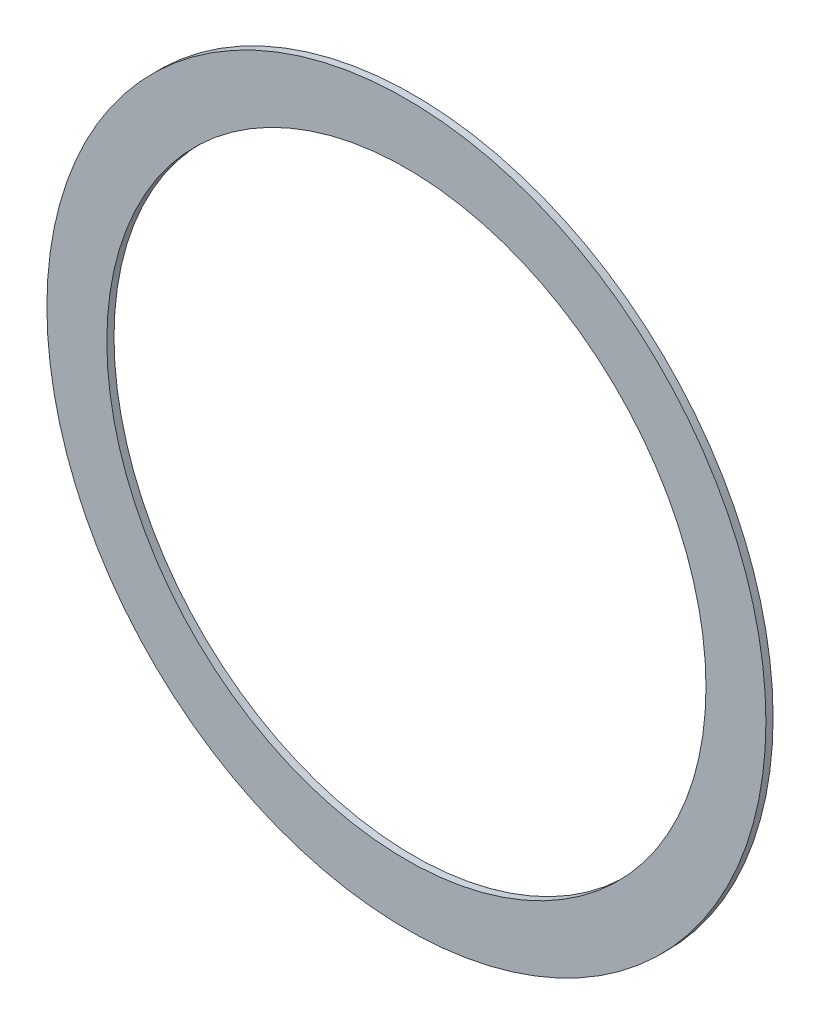
SolidWorks part; units mm, degrees
material "VITON"
ref_plane "Front" through (0, 0, 0) normal (0, 0, 1) x (1, 0, 0)
ref_plane "Top" through (0, 0, 0) normal (0, 1, 0) x (1, 0, 0)
ref_plane "Right" through (0, 0, 0) normal (1, 0, 0) x (0, 0, -1)
sketch "Sketch1" plane through (0, 0, 0) normal (0, 0, 1) x (1, 0, 0)
  circle A0 centre (0, 0) radius 15.875
  circle A1 centre (0, 0) radius 19.05
  dimension "D1" = 38.1
  dimension "D2" = 31.75
extrude "Boss-Extrude1" add sketch "Sketch1" along normal blind 0.381
